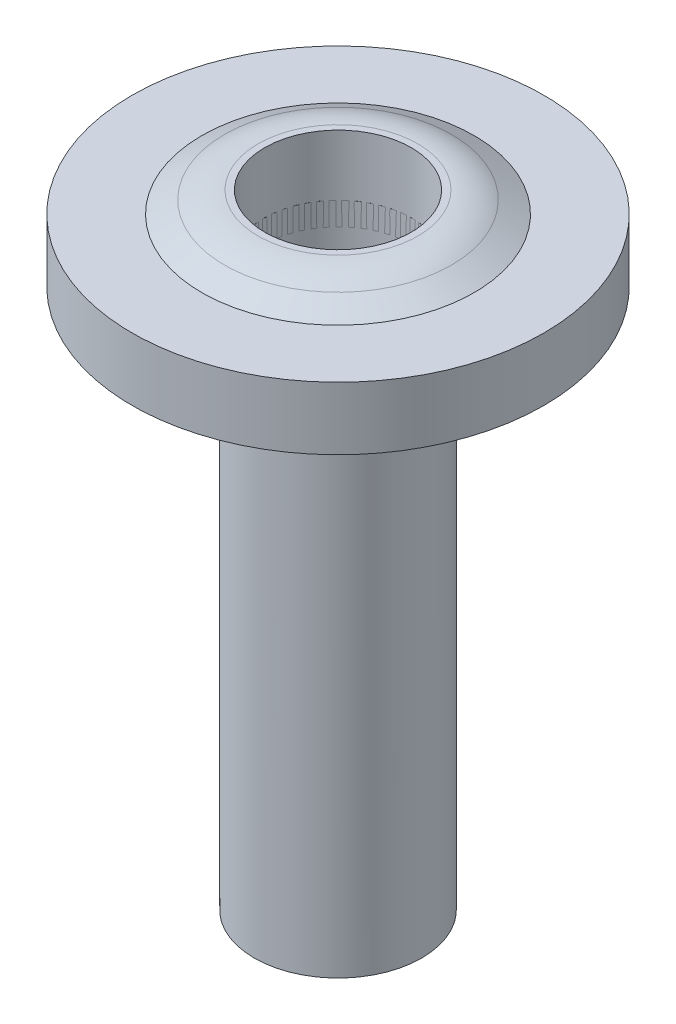
SolidWorks part; units mm, degrees
ref_plane "Alzado" through (0, 0, 0) normal (0, 0, 1) x (1, 0, 0)
ref_plane "Planta" through (0, 0, 0) normal (0, 1, 0) x (1, 0, 0)
ref_plane "Vista lateral" through (0, 0, 0) normal (1, 0, 0) x (0, 0, -1)
sketch "Croquis1" plane through (0, 0, 0) normal (0, 0, 1) x (1, 0, 0)
  line L0 (12, 0) -> (12, 69.3)
  line L1 (12, 69.3) -> (25, 69.3)
  line L2 (25, 69.3) -> (25, 73.3)
  line L3 (25, 73.3) -> (0, 73.3)
  line L4 (0, 0) -> (0, 73.3) construction
  line L5 (0, 73.3) -> (0, 0)
  line L6 (0, 0) -> (12, 0)
  dimension "D1" = 69.3
  dimension "D2" = 12
  dimension "D3" = 25
  dimension "D4" = 4
revolve "Revolución1" add sketch "Croquis1" angle 360 about L5
sketch "Croquis3" plane through (0, 0, 0) normal (0, 0, 1) x (1, 0, 0)
  line L0 (0, 73.3) -> (0, 90.8613) construction
  line L1 (25, 73.3) -> (-25, 73.3) construction
  line L2 (0, 77.3) -> (28.5, 77.3)
  line L5 (0, 70) -> (0, 77.3)
  line L6 (28.5, 77.3) -> (28.5, 70)
  line L7 (28.5, 70) -> (0, 70)
  dimension "D1" = 4
  dimension "D2" = 28.5
revolve "Revolución2" add sketch "Croquis3" angle 360 about L5
fillet "Redondeo1" radius 2 1 edges at (0, 77.3, -28.5)
sketch "Croquis6" plane through (0, 0, 0) normal (0, 0, 1) x (1, 0, 0)
  line L0 (0, 70) -> (0, 92.0068) construction
  line L1 (-28.5, 70) -> (28.5, 70) construction
  line L2 (0, 70) -> (29.5, 70)
  line L3 (29.5, 70) -> (29.5, 79)
  line L4 (29.5, 79) -> (19.5, 79)
  line L5 (0, 82) -> (11.4501, 82)
  line L6 (16.2386, 80.779) -> (19.5, 79)
  line L7 (0, 82) -> (0, 70)
  arc A0 (11.4501, 82) -> (16.2386, 80.779) centre (11.4501, 72) cw
  point P12 (14, 82)
  dimension "D6" = 10
  dimension "D1" = 29.5
  dimension "D2" = 19.5
  dimension "D3" = 9
  dimension "D4" = 12
  dimension "D5" = 14
revolve "Revolución4" add sketch "Croquis6" angle 360 about L7
sketch "Croquis7" plane through (0, 82, 0) normal (0, 1, 0) x (1, 0, 0)
  circle A0 centre (0, 0) radius 10.5
  dimension "D1" = 21
extrude "Cortar-Extruir2" cut sketch "Croquis7" against normal through all
sketch "Croquis8" plane through (0, 0, 0) normal (0, -1, 0) x (1, 0, 0)
  circle A0 centre (0, 0) radius 12
  circle A1 centre (0, 0) radius 10.5
extrude "Saliente-Extruir1" add sketch "Croquis8" along normal blind 7.3
